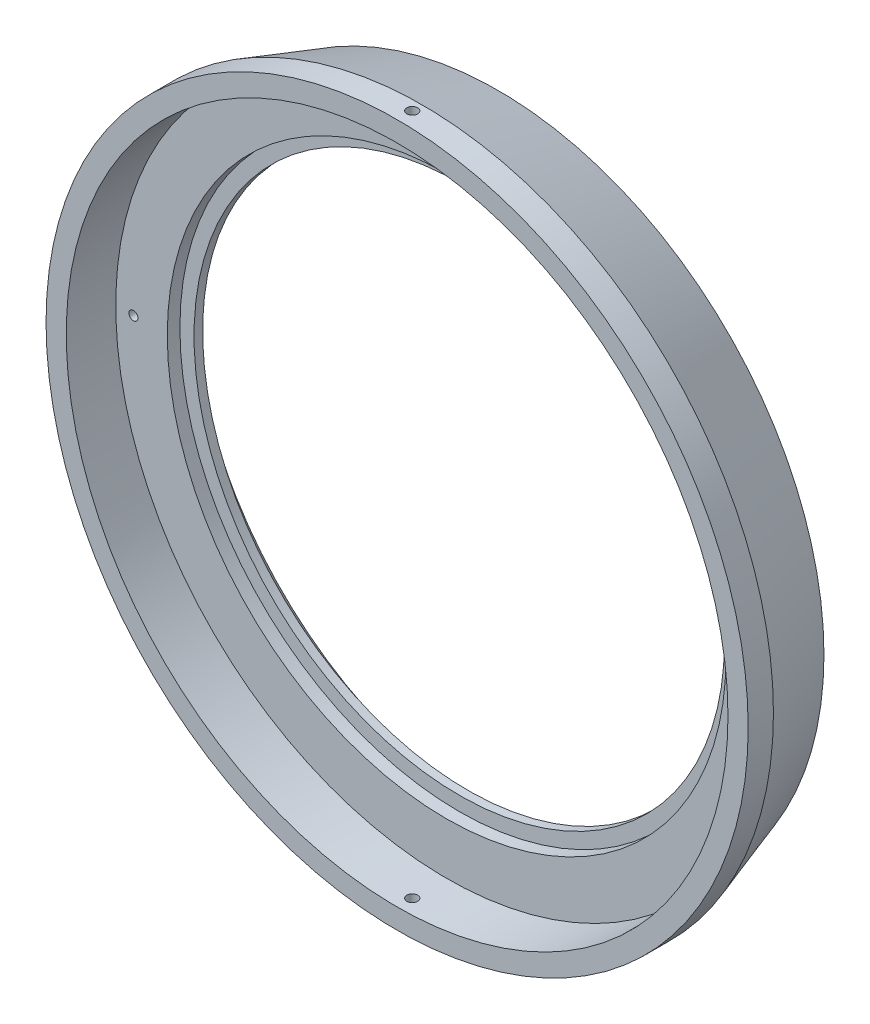
SolidWorks part; units mm, degrees
ref_plane "Front Plane" through (0, 0, 0) normal (0, 0, 1) x (1, 0, 0)
ref_plane "Top Plane" through (0, 0, 0) normal (0, 1, 0) x (1, 0, 0)
ref_plane "Right Plane" through (0, 0, 0) normal (1, 0, 0) x (0, 0, -1)
sketch "Sketch1" plane through (0, 0, 0) normal (0, 0, 1) x (1, 0, 0)
  circle A0 centre (0, 0) radius 88.265
  dimension "D1" = 176.53
extrude "Boss-Extrude1" add sketch "Sketch1" along normal blind 25.4
sketch "Sketch2" plane through (0, 0, 25.4) normal (0, 0, 1) x (1, 0, 0)
  circle A0 centre (0, 0) radius 83.185
  dimension "D1" = 166.37
extrude "Cut-Extrude1" cut sketch "Sketch2" against normal blind 9.144
sketch "Sketch3" plane through (0, 0, 16.256) normal (0, 0, 1) x (1, 0, 0)
  circle A0 centre (0, 0) radius 76.2
  dimension "D1" = 152.4
extrude "Cut-Extrude2" cut sketch "Sketch3" against normal blind 3.302
sketch "Sketch4" plane through (0, 0, 12.954) normal (0, 0, 1) x (1, 0, 0)
  circle A0 centre (0, 0) radius 70.231
  dimension "D1" = 140.462
extrude "Cut-Extrude3" cut sketch "Sketch4" against normal blind 3.175
sketch "Sketch6" plane through (0, 0, 9.779) normal (0, 0, 1) x (1, 0, 0)
  circle A0 centre (0, 0) radius 66.675
  dimension "D1" = 133.35
extrude "Cut-Extrude5" cut sketch "Sketch6" against normal through all
sketch "Sketch7" plane through (0, 0, 16.256) normal (0, 0, 1) x (1, 0, 0)
  circle A0 centre (0, 0) radius 83.185
extrude "Cut-Extrude6" cut sketch "Sketch7" against normal up to surface (3.302 mm away) up to face at (70.231, 0, 12.954)
chamfer "Chamfer2" distance 6.35 distance2 19.05 1 edges at (88.265, 0, 0)
chamfer "Chamfer1" distance 7.62 distance2 10.16 1 edges at (66.675, 0, 0)
sketch "Sketch5" plane through (0, 0, 0) normal (0, 1, 0) x (1, 0, 0)
  line L1 (-88.265, -25.4) -> (88.265, -25.4) construction
  circle A0 centre (0, -21.59) radius 1.3525
  dimension "D1" = 2.7051
  dimension "D2" = 3.81
extrude "Cut-Extrude4" cut sketch "Sketch5" against normal through all both and the other way through all
hole_wizard "Tap Drill for #4-40 Tap1" positions "Sketch8" profile "Sketch9" hole size "#4-40" standard "ANSI Inch"
sketch "Sketch8" plane through (0, 0, 12.954) normal (0, 0, 1) x (1, 0, 0)
  line L4 (-66.675, 0) -> (-83.185, 0) construction
  line L6 (0, -13.97) -> (0, 13.97) construction
  line L7 (66.675, 0) -> (83.185, 0) construction
  circle A2 centre (0, 0) radius 66.675 construction
  circle A3 centre (0, 0) radius 83.185 construction
  point P19 (-78.74, 0)
  point P30 (0, 0)
  point P36 (78.74, 0)
  dimension "D1" = 4.445
  dimension "D2" = 78.74
sketch "Sketch9" plane through (-78.74, 0, 12.954) normal (1, 0, 0) x (0, -1, 0)
  line L0 (0, 0) -> (0, 7.0292)
  line L1 (0, 7.0292) -> (1.1303, 6.35)
  line L2 (1.1303, 6.35) -> (1.1303, 0)
  line L5 (1.1303, 0) -> (0, 0)
  line L10 (0, 7.0292) -> (-1.1303, 6.35) construction
  line L11 (0, -6.35) -> (0, 107.95) construction
  dimension "Hole Dia." = 2.2606
  dimension "Hole Depth" = 6.35
  dimension "Drill Angle" = 118
